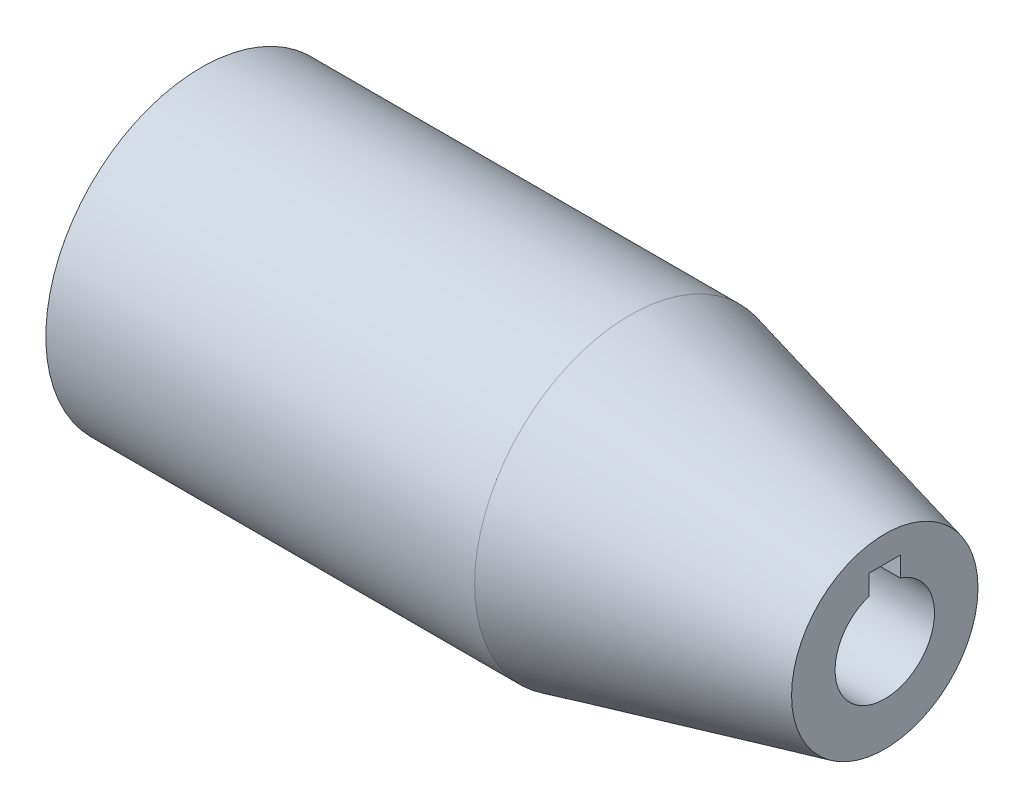
SolidWorks part; units mm, degrees
ref_plane "Спереди" through (0, 0, 0) normal (0, 0, 1) x (1, 0, 0)
ref_plane "Сверху" through (0, 0, 0) normal (0, 1, 0) x (1, 0, 0)
ref_plane "Справа" through (0, 0, 0) normal (1, 0, 0) x (0, 0, -1)
sketch "Эскиз2" plane through (0, 0, 0) normal (1, 0, 0) x (0, 0, -1)
  line L1 (0, 5) -> (2.5, 5)
  line L2 (0, 5) -> (-2.5, 5)
  line L4 (0, 10.8) -> (2.5, 10.8)
  line L5 (2.5, 10.8) -> (2.5, 5)
  line L6 (0, 10.8) -> (-2.5, 10.8)
  line L7 (-2.5, 10.8) -> (-2.5, 5)
  circle A0 centre (0, 0) radius 8
  circle A1 centre (0, 0) radius 15
  point P4 (0, 8)
  point P5 (0, 8)
  point P6 (0, 8)
  point P7 (0, 8)
  dimension "D1" = 16
  dimension "D2" = 30
extrude "Бобышка-Вытянуть2" add sketch "Эскиз2" along normal blind 41
sketch "Эскиз5" plane through (0, 0, 0) normal (1, 0, 0) x (0, 0, -1)
  circle A0 centre (0, 0) radius 25
extrude "Бобышка-Вытянуть4" add sketch "Эскиз5" against normal blind 9
sketch "Эскиз6" plane through (0, 0, 0) normal (1, 0, 0) x (0, 0, -1)
  line L1 (0, 10) -> (-4, 10)
  line L2 (0, 10) -> (4, 10)
  line L4 (0, 17.3) -> (-4, 17.3)
  line L5 (-4, 17.3) -> (-4, 10)
  line L6 (0, 17.3) -> (4, 17.3)
  line L7 (4, 17.3) -> (4, 10)
  circle A0 centre (0, 0) radius 25
  circle A1 centre (0, 0) radius 14
extrude "Бобышка-Вытянуть5" add sketch "Эскиз6" against normal blind 60 from offset 9 contours A0 A1 L5 L4 L6 L7 offset against normal yes
sketch "Эскиз7" plane through (0, 0, 0) normal (0, 1, 0) x (1, 0, 0)
  line L0 (0, 25) -> (0, 15)
  line L1 (0, 15) -> (41, 15)
  line L2 (41, 15) -> (0, 25)
  line L3 (0, 25) -> (0.1285, 24.9716)
  line L5 (-60.1971, 0) -> (0, 0)
revolve "Повернуть1" add sketch "Эскиз7" angle 360 about L5
